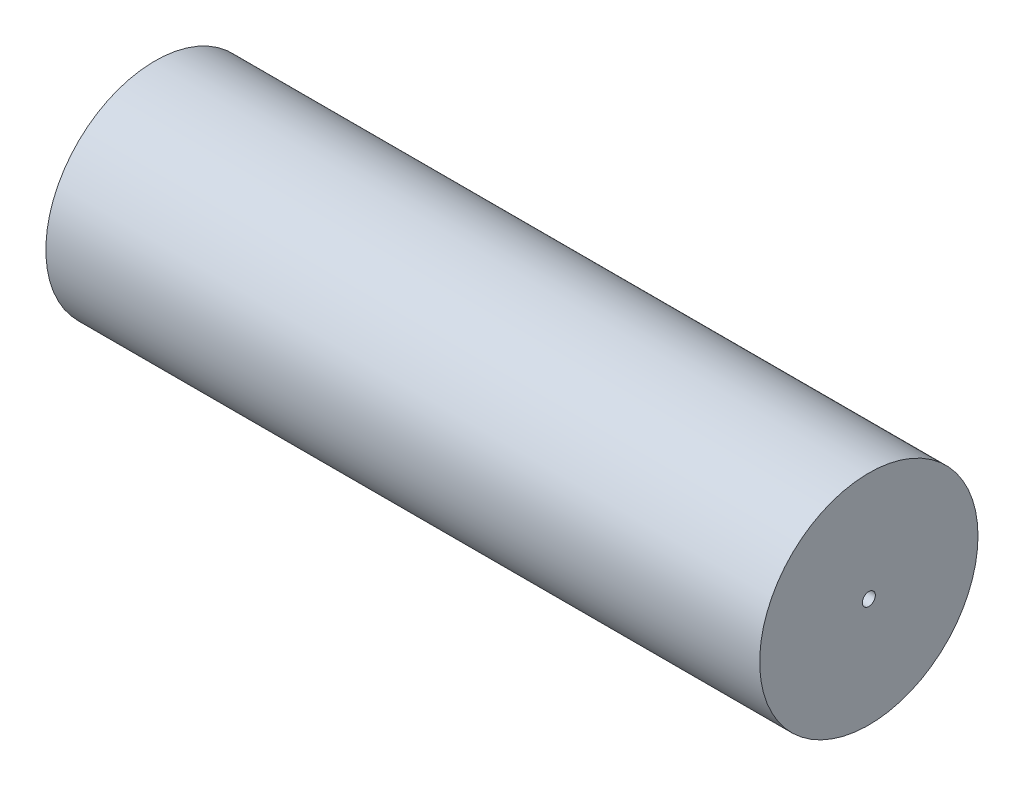
SolidWorks part; units mm, degrees
ref_plane "Front Plane" through (0, 0, 0) normal (0, 0, 1) x (1, 0, 0)
ref_plane "Top Plane" through (0, 0, 0) normal (0, 1, 0) x (1, 0, 0)
ref_plane "Right Plane" through (0, 0, 0) normal (1, 0, 0) x (0, 0, -1)
sketch "Sketch1" plane through (0, 0, 0) normal (1, 0, 0) x (0, 0, -1)
  circle A0 centre (0, 0) radius 26
  dimension "D1" = 52
extrude "Boss-Extrude1" add sketch "Sketch1" along normal blind 170
sketch "Sketch2" plane through (170, 0, 0) normal (1, 0, 0) x (0, 0, -1)
  circle A0 centre (0, 0) radius 1.55
  dimension "D1" = 3.1
extrude "Cut-Extrude1" cut sketch "Sketch2" against normal blind 5
sketch "Sketch3" plane through (0, 0, 0) normal (-1, 0, 0) x (0, 0, 1)
  circle A0 centre (0, 0) radius 1.5
  dimension "D1" = 3
extrude "Cut-Extrude2" cut sketch "Sketch3" against normal blind 5
